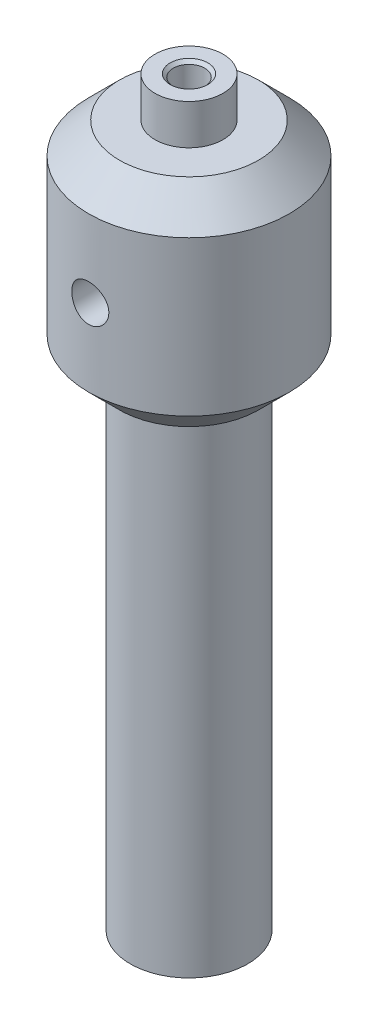
SolidWorks part; units mm, degrees
material "Plain Carbon Steel"
ref_plane "Front Plane" through (0, 0, 0) normal (0, 0, 1) x (1, 0, 0)
ref_plane "Top Plane" through (0, 0, 0) normal (0, 1, 0) x (1, 0, 0)
ref_plane "Right Plane" through (0, 0, 0) normal (1, 0, 0) x (0, 0, -1)
sketch "Sketch1" plane through (0, 0, 0) normal (0, 0, 1) x (1, 0, 0)
  line L0 (0, 0) -> (0, 240)
  line L1 (0, 240) -> (11, 240)
  line L2 (11, 240) -> (11, 227)
  line L3 (11, 227) -> (22.5, 227)
  line L4 (22.5, 227) -> (32.5, 217)
  line L5 (32.5, 217) -> (32.5, 167)
  line L6 (32.5, 167) -> (22.5, 157)
  line L7 (22.5, 157) -> (19, 157)
  line L8 (19, 157) -> (19, 0)
  line L9 (19, 0) -> (0, 0)
  point P3 (19.6553, 157)
  dimension "D1" = 240
  dimension "D2" = 11
  dimension "D3" = 13
  dimension "D4" = 10
  dimension "D5" = 10
  dimension "D6" = 83
  dimension "D7" = 32.5
  dimension "D8" = 19
  dimension "D9" = 45
revolve "Revolve1" add sketch "Sketch1" angle 360 about L0
cosmetic thread "Cosmetic Thread1" parameters "D1"=154, "D2"=31.61
hole_wizard "M12 Tapped Hole1" positions "3DSketch1" profile "Sketch3" tap size "M12" standard "DIN"
sketch3d "3DSketch1"
  line L0 (0, 240, 0) -> (0, 227, 0) construction
  point P0 (0, 240, 0)
sketch "Sketch3" plane through (0, 240, 0) normal (1, 0, 0) x (0, 0, 1)
  line L0 (0, 0) -> (0, 38.0644)
  line L1 (0, 38.0644) -> (5.1, 35)
  line L2 (5.1, 35) -> (5.1, 0)
  line L5 (5.1, 0) -> (0, 0)
  line L10 (0, 38.0644) -> (-5.1, 35) construction
  line L11 (0, -6.35) -> (0, 107.95) construction
  dimension "Tap Drill Dia." = 10.2
  dimension "Tap Drill Depth" = 35
  dimension "Drill Angle" = 118
cosmetic thread "Hole Thread1" parameters "D1"=30, "D2"=12
sketch "Sketch4" plane through (0, 0, 0) normal (0, 0, 1) x (1, 0, 0)
  line L0 (-19, 157) -> (19, 157) construction
  circle A0 centre (0, 192) radius 6
  point P2 (0, 0)
  dimension "D1" = 12
  dimension "D2" = 35
extrude "Cut-Extrude1" cut sketch "Sketch4" against normal through all both and the other way through all
chamfer "Chamfer1" distance 1 angle 45 1 edges at (0, 240, 5.1)
